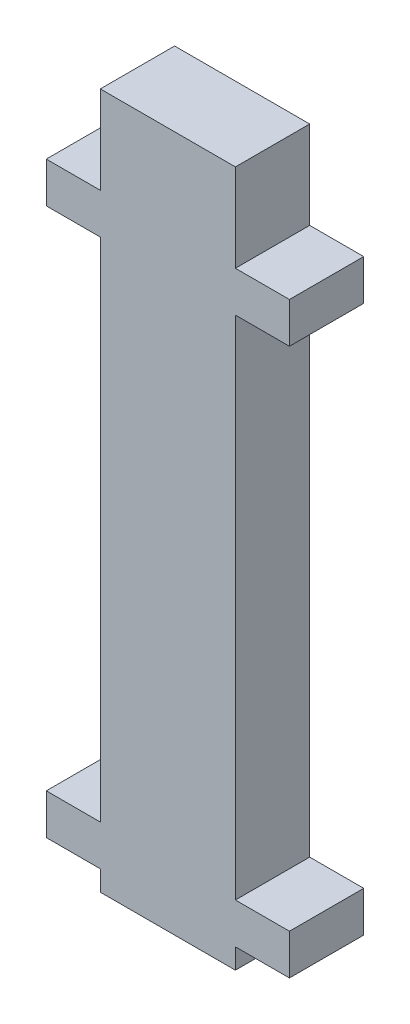
SolidWorks part; units mm, degrees
ref_plane "Plan de face" through (0, 0, 0) normal (0, 0, 1) x (1, 0, 0)
ref_plane "Plan de dessus" through (0, 0, 0) normal (0, 1, 0) x (1, 0, 0)
ref_plane "Plan de droite" through (0, 0, 0) normal (1, 0, 0) x (0, 0, -1)
sketch "Esquisse1" plane through (0, 0, 0) normal (0, 0, 1) x (1, 0, 0)
  line L0 (10, 50.5) -> (10, 0) construction
  line L1 (0, 0) -> (20, 0) construction
  line L2 (0, 0) -> (0, 54) construction
  line L3 (0, 81) -> (0, 6)
  line L4 (20, 0) -> (20, 54) construction
  line L5 (20, 81) -> (20, 6)
  line L6 (3, 30) -> (3, 0) construction
  line L7 (17, 30) -> (17, 0) construction
  line L8 (0, 54) -> (0, 6) construction
  line L9 (0, 6) -> (-8, 6)
  line L10 (-8, 6) -> (-8, 0)
  line L11 (-8, 0) -> (0, 0)
  line L12 (0, 0) -> (0, -3)
  line L13 (0, -3) -> (20, -3)
  line L14 (20, -3) -> (20, 0)
  line L15 (20, 0) -> (28, 0)
  line L16 (28, 0) -> (28, 6)
  line L17 (28, 6) -> (20, 6)
  line L18 (20, 6) -> (20, 54) construction
  line L20 (20, 81) -> (28, 81)
  line L21 (28, 81) -> (28, 87)
  line L22 (28, 87) -> (20, 87)
  line L23 (20, 87) -> (20, 100)
  line L24 (5, 100) -> (15, 100)
  line L25 (0, 100) -> (0, 87)
  line L26 (0, 87) -> (-8, 87)
  line L27 (-8, 87) -> (-8, 81)
  line L28 (-8, 81) -> (0, 81)
  line L30 (0, 100) -> (5, 100)
  line L31 (5, 100) -> (5, 110) construction
  line L32 (5, 110) -> (15, 110) construction
  line L33 (15, 110) -> (15, 100) construction
  line L34 (15, 100) -> (20, 100)
  line L35 (10, 107.5) -> (10, -3) construction
  line L44 (-18.4801, 73) -> (50.2693, 73) construction
  circle A0 centre (10, 58) radius 51.5 construction
  dimension "D23" = 15
  dimension "D3" = 20
  dimension "D4" = 13
  dimension "D9" = 75
  dimension "D10" = 6
  dimension "D11" = 8
  dimension "D12" = 3
  dimension "D13" = 6
  dimension "D18" = 10
  dimension "D22" = 14
extrude "Boss.-Extru.1" add sketch "Esquisse1" along normal blind 11
sketch "Esquisse2" plane through (0, 0, 11) normal (0, 0, 1) x (1, 0, 0)
  circle A0 centre (-8.0125, 12.9998) radius 1.15
  circle A1 centre (38.0125, 12.9998) radius 1.15
  circle A2 centre (31.215, 12.9998) radius 1.15
  circle A3 centre (-1.215, 12.9998) radius 1.15
  dimension "D1" = 2.3
